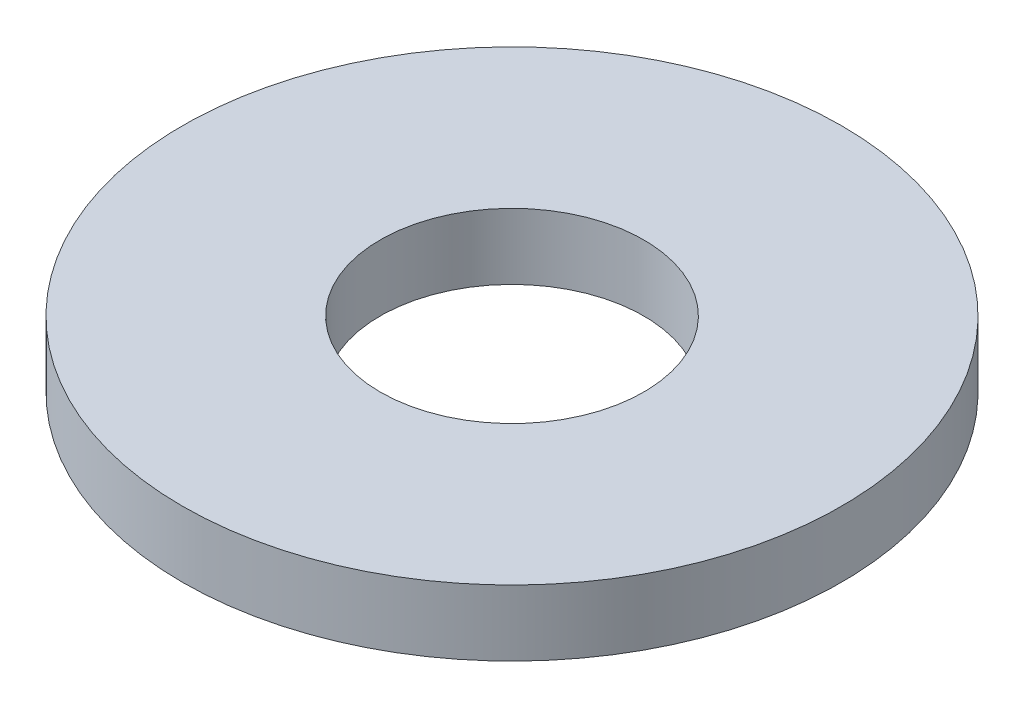
SolidWorks part; units mm, degrees
material "AISI 304"
ref_plane "Front Plane" through (0, 0, 0) normal (0, 0, 1) x (1, 0, 0)
ref_plane "Top Plane" through (0, 0, 0) normal (0, 1, 0) x (1, 0, 0)
ref_plane "Right Plane" through (0, 0, 0) normal (1, 0, 0) x (0, 0, -1)
sketch "Sketch1" plane through (0, 0, 0) normal (0, 1, 0) x (1, 0, 0)
  circle A0 centre (0, 0) radius 5
  circle A1 centre (0, 0) radius 2
  dimension "D1" = 4
  dimension "D2" = 10
extrude "Boss-Extrude1" add sketch "Sketch1" along normal blind 1
